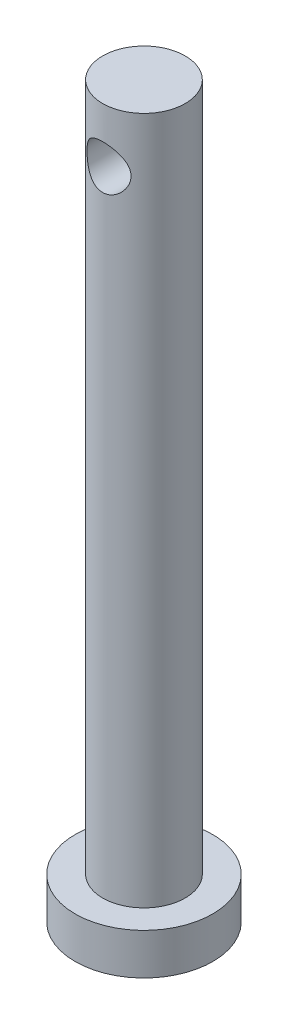
SolidWorks part; units mm, degrees
ref_plane "前视基准面" through (0, 0, 0) normal (0, 0, 1) x (1, 0, 0)
ref_plane "上视基准面" through (0, 0, 0) normal (0, 1, 0) x (1, 0, 0)
ref_plane "右视基准面" through (0, 0, 0) normal (1, 0, 0) x (0, 0, -1)
sketch "草图1" plane through (0, 0, 0) normal (0, 1, 0) x (1, 0, 0)
  circle A0 centre (0, 0) radius 2.5
  dimension "D1" = 5
extrude "凸台-拉伸1" add sketch "草图1" along normal blind 1.5
sketch "草图2" plane through (0, 1.5, 0) normal (0, 1, 0) x (1, 0, 0)
  circle A0 centre (0, 0) radius 1.5
  dimension "D1" = 3
extrude "凸台-拉伸2" add sketch "草图2" along normal blind 25
sketch "草图3" plane through (0, 0, 0) normal (0, 0, 1) x (1, 0, 0)
  line L0 (1.5, 26.5) -> (-1.5, 26.5) construction
  circle A0 centre (0, 24.5) radius 0.8
  dimension "D1" = 1.6
  dimension "D2" = 2
extrude "切除-拉伸1" cut sketch "草图3" against normal mid plane 10
